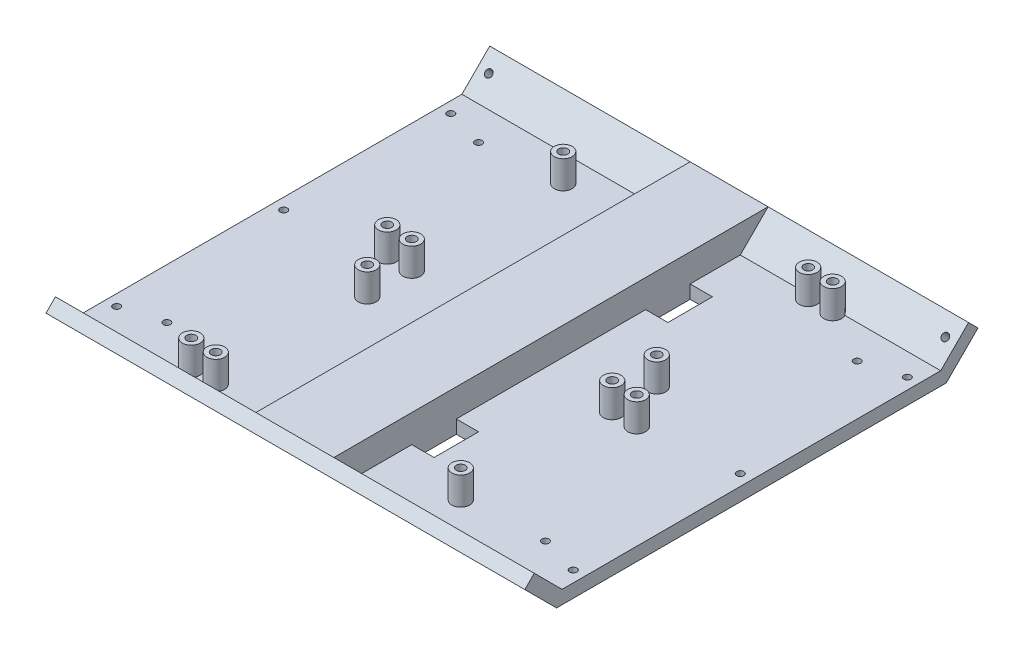
SolidWorks part; units mm, degrees
ref_plane "Front Plane" through (0, 0, 0) normal (0, 0, 1) x (1, 0, 0)
ref_plane "Top Plane" through (0, 0, 0) normal (0, 1, 0) x (1, 0, 0)
ref_plane "Right Plane" through (0, 0, 0) normal (1, 0, 0) x (0, 0, -1)
sketch "Sketch2" plane through (0, 0, 0) normal (1, 0, 0) x (0, 0, -1)
  line L0 (-85, 0) -> (85, 0)
  line L1 (85, 0) -> (97.5, 12.5)
  line L2 (-85, 0) -> (-97.5, 12.5)
  line L8 (-87.4853, -6) -> (-101.7426, 8.2574)
  line L9 (-87.4853, -6) -> (87.4853, -6)
  line L10 (87.4853, -6) -> (101.7426, 8.2574)
  line L11 (-101.7426, 8.2574) -> (-97.5, 12.5)
  line L12 (97.5, 12.5) -> (101.7426, 8.2574)
  line L13 (-97.5, 12.5) -> (-110, 25) construction
  line L14 (97.5, 12.5) -> (110, 25) construction
  point P4 (0, 0)
  dimension "D2" = 135
  dimension "D3" = 135
  dimension "D1" = 220
  dimension "D4" = 25
  dimension "D5" = 6
extrude "Main" add sketch "Sketch2" along normal mid plane 215
hole_wizard "Ø3.0mm Dowel Hole1" positions "3DSketch1" profile "Sketch3" hole size "Ø4.0" standard "ANSI Metric" end condition through all
sketch3d "3DSketch1"
  line L0 (-107.5, 7.0711, -92.0711) -> (-102.5, 7.0711, -92.0711) construction
  line L1 (-107.5, 12.5, -97.5) -> (-107.5, 0, -85) construction
  line L2 (-102.5, 7.0711, -92.0711) -> (-102.5, 0, -85) construction
  line L3 (107.5, 0, -85) -> (-107.5, 0, -85) construction
  line L4 (-102.5, 0, -85) -> (-102.5, 0, -75) construction
  line L5 (-102.5, 0, -75) -> (-102.5, 0, 0) construction
  line L6 (-102.5, 0, 0) -> (-102.5, 0, 75) construction
  line L7 (-102.5, 0, 75) -> (-102.5, 0, 85) construction
  line L8 (107.5, 0, 85) -> (-107.5, 0, 85) construction
  line L13 (-102.5, 0, 85) -> (-102.5, 7.0711, 92.0711) construction
  line L14 (-102.5, 7.0711, 92.0711) -> (-107.5, 7.0711, 92.0711) construction
  line L15 (-107.5, 0, 85) -> (-107.5, 12.5, 97.5) construction
  line L20 (102.5, 0, -85) -> (102.5, 0, -75) construction
  line L21 (102.5, 0, -75) -> (102.5, 0, 0) construction
  line L22 (102.5, 0, 0) -> (102.5, 0, 75) construction
  line L23 (102.5, 0, 75) -> (102.5, 0, 85) construction
  line L24 (102.5, 0, 85) -> (102.5, 7.0711, 92.0711) construction
  line L25 (102.5, 7.0711, 92.0711) -> (107.5, 7.0711, 92.0711) construction
  line L26 (107.5, 0, 85) -> (107.5, 12.5, 97.5) construction
  line L28 (102.5, 0, -85) -> (102.5, 7.0711, -92.0711) construction
  line L29 (102.5, 7.0711, -92.0711) -> (107.5, 7.0711, -92.0711) construction
  line L30 (107.5, 12.5, -97.5) -> (107.5, 0, -85) construction
  line L32 (107.5, 0, 85) -> (102.5, 0, 85) construction
  line L34 (-102.5, 0, 85) -> (-107.5, 0, 85) construction
  point P0 (-102.5, 7.0711, -92.0711)
  point P2 (-102.5, 0, -75)
  point P4 (-102.5, 0, 0)
  point P6 (-102.5, 0, 75)
  point P8 (-102.5, 7.0711, 92.0711)
  point P10 (102.5, 7.0711, 92.0711)
  point P12 (102.5, 0, 75)
  point P14 (102.5, 0, 0)
  point P16 (102.5, 0, -75)
  point P18 (102.5, 7.0711, -92.0711)
  dimension "D1" = 5
  dimension "D2" = 10
  dimension "D3" = 10
sketch "Sketch3" plane through (-102.5, 7.0711, -92.0711) normal (1, 0, 0) x (0, -0.7071, 0.7071)
  line L0 (0, 0) -> (0, 16.0815)
  line L1 (0, 16.0815) -> (1.6, 16.0815)
  line L2 (1.6, 16.0815) -> (1.6, 0)
  line L5 (1.6, 0) -> (0, 0)
  line L11 (0, -6.35) -> (0, 107.95) construction
  dimension "Thru Hole Dia." = 3.2
  dimension "Thru Hole Depth" = 16.0815
sketch "Sketch4" plane through (0, 0, 0) normal (0, 1, 0) x (1, 0, 0)
  line L0 (0, -85) -> (0, 85) construction
  line L5 (107.5, -85) -> (-107.5, -85) construction
  line L7 (107.5, 85) -> (-107.5, 85) construction
  line L8 (0, 0) -> (107.5, 0) construction
  line L9 (107.5, 85) -> (107.5, -85) construction
  line L11 (17.5, 62.5) -> (27.5, 62.5)
  line L12 (17.5, 62.5) -> (17.5, 42.5)
  line L13 (17.5, 42.5) -> (27.5, 42.5)
  line L14 (27.5, 62.5) -> (27.5, 42.5)
  line L15 (17.5, 62.5) -> (27.5, 42.5) construction
  line L16 (17.5, 42.5) -> (27.5, 62.5) construction
  point P10 (22.5, 52.5)
  dimension "D1" = 20
  dimension "D2" = 10
  dimension "D3" = 35
  dimension "D4" = 125
extrude "Battery strap cutout" cut sketch "Sketch4" against normal through all
mirror "Battery strap cutout mirror" about plane through (0, 0, 0) normal (1, 0, 0) of "Battery strap cutout" second plane through (0, 0, 0) second plane normal (0, 0, 1)
sketch "Sketch6" plane through (0, 0, 0) normal (1, 0, 0) x (0, 0, -1)
  line L0 (-97.5, 12.5) -> (97.5, 12.5)
  line L1 (-85, 0) -> (-97.5, 12.5) construction
  line L2 (97.5, 12.5) -> (85, 0) construction
  line L3 (85, 0) -> (-85, 0) construction
  line L4 (-85, 0) -> (-97.5, 12.5)
  line L5 (85, 0) -> (-85, 0)
  line L6 (97.5, 12.5) -> (85, 0)
extrude "Battery mount" add sketch "Sketch6" along normal mid plane 35
sketch "Sketch7" plane through (0, 12.5, 0) normal (0, 1, 0) x (1, 0, 0)
  line L0 (-61, -15) -> (-50, -15) construction
  line L1 (-61, -15) -> (-61, -83) construction
  line L2 (-61, -83) -> (-50, -83) construction
  line L3 (-50, -15) -> (-50, -83) construction
  line L4 (-61, -15) -> (-50, -83) construction
  line L5 (-61, -83) -> (-50, -15) construction
  line L6 (-61, 73) -> (-50, 73) construction
  line L7 (-61, 73) -> (-61, 5) construction
  line L8 (-61, 5) -> (-50, 5) construction
  line L9 (-50, 73) -> (-50, 5) construction
  line L10 (-61, 73) -> (-50, 5) construction
  line L11 (-61, 5) -> (-50, 73) construction
  line L12 (50, 83) -> (61, 83) construction
  line L13 (50, 83) -> (50, 15) construction
  line L14 (50, 15) -> (61, 15) construction
  line L15 (61, 83) -> (61, 15) construction
  line L16 (50, 83) -> (61, 15) construction
  line L17 (50, 15) -> (61, 83) construction
  line L18 (50, -5) -> (61, -5) construction
  line L19 (50, -5) -> (50, -73) construction
  line L20 (50, -73) -> (61, -73) construction
  line L21 (61, -5) -> (61, -73) construction
  line L22 (50, -5) -> (61, -73) construction
  line L23 (50, -73) -> (61, -5) construction
  circle A0 centre (-50, -15) radius 4
  circle A1 centre (-50, -83) radius 4
  circle A2 centre (-61, -83) radius 4
  circle A3 centre (-50, 73) radius 4
  circle A4 centre (-50, 5) radius 4
  circle A5 centre (-61, 5) radius 4
  circle A6 centre (61, 83) radius 4
  circle A7 centre (50, 83) radius 4
  circle A8 centre (50, 15) radius 4
  circle A9 centre (61, -5) radius 4
  circle A10 centre (50, -5) radius 4
  circle A11 centre (50, -73) radius 4
  point P0 (-55.5, -49)
  point P8 (55.5, 49)
  point P9 (-55.5, 39)
  point P18 (55.5, -39)
  dimension "D3" = 8
  dimension "D1" = 68
  dimension "D2" = 11
  dimension "D4" = 5
  dimension "D5" = 15
  dimension "D6" = 15
  dimension "D7" = 5
  dimension "D8" = 50
  dimension "D9" = 50
extrude "PCB mounts" add sketch "Sketch7" against normal up to surface (12.5 mm away) up to face at (35.8333, 0, 0)
sketch "Sketch8" plane through (0, 12.5, 0) normal (0, 1, 0) x (1, 0, 0)
  circle A0 centre (-50, 73) radius 2.05
  circle A1 centre (-50, 5) radius 2.05
  circle A2 centre (-61, 5) radius 2.05
  circle A3 centre (-50, -15) radius 2.05
  circle A4 centre (-61, -83) radius 2.05
  circle A5 centre (-50, -83) radius 2.05
  circle A6 centre (50, -73) radius 2.05
  circle A7 centre (61, -5) radius 2.05
  circle A8 centre (50, -5) radius 2.05
  circle A9 centre (50, 15) radius 2.05
  circle A10 centre (61, 83) radius 2.05
  circle A11 centre (50, 83) radius 2.05
  dimension "D1" = 4.1
extrude "PCB mount inserts" cut sketch "Sketch8" against normal blind 5.7
sketch "Sketch9" plane through (0, -6, 0) normal (0, -1, 0) x (1, 0, 0)
  circle A0 centre (85, 70) radius 1.6
  dimension "D1" = 3.2
  dimension "D2" = 85
  dimension "D3" = 70
extrude "Feet screw hole" cut sketch "Sketch9" against normal through all
mirror "Mirror1" about plane through (0, 0, 0) normal (0, 0, 1) of "Feet screw hole" second plane through (0, 0, 0) second plane normal (1, 0, 0)
equation "\"length\" = 215mm"
equation "\"D1@Main\" = \"length\""
equation "\"width\" = 220mm"
equation "\"height\" = 100mm"
equation "\"skin_th\" = 6mm"
equation "\"D5@Sketch2\"=\"skin_th\""
equation "\"D1@Sketch2\"=\"width\""
